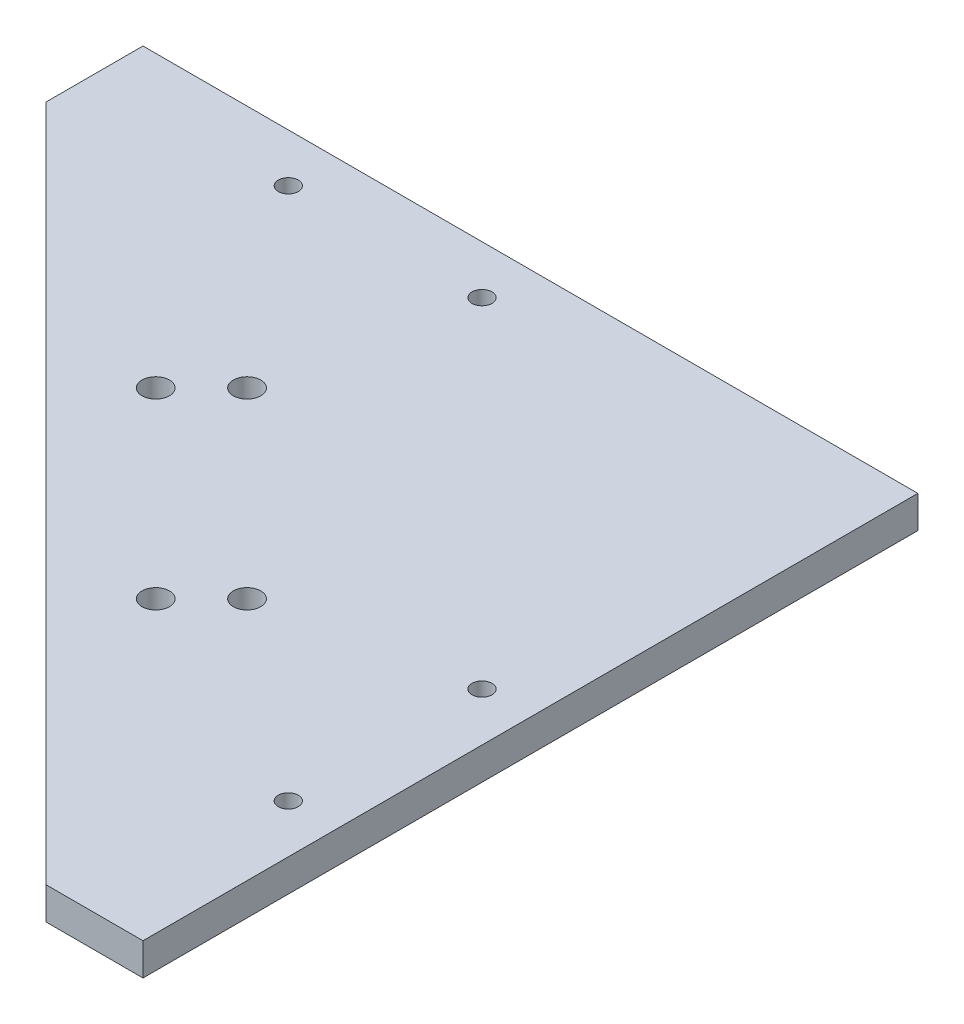
SolidWorks part; units mm, degrees
ref_plane "Front Plane" through (0, 0, 0) normal (0, 0, 1) x (1, 0, 0)
ref_plane "Top Plane" through (0, 0, 0) normal (0, 1, 0) x (1, 0, 0)
ref_plane "Right Plane" through (0, 0, 0) normal (1, 0, 0) x (0, 0, -1)
sketch "Sketch2" plane through (0, 0, 0) normal (0, 1, 0) x (1, 0, 0)
  line L0 (-120, -15) -> (-15, -120)
  line L1 (0, 0) -> (-120, 0)
  line L2 (0, 0) -> (0, -120)
  line L3 (0, -120) -> (-15, -120)
  line L4 (-120, 0) -> (-120, -15)
  dimension "D1" = 120
  dimension "D2" = 120
  dimension "D3" = 15
  dimension "D4" = 15
extrude "Boss-Extrude1" add sketch "Sketch2" along normal blind 5
sketch "Sketch3" plane through (0, 5, 0) normal (0, 1, 0) x (1, 0, 0)
  line L0 (-120, -7.5) -> (8.5201, -7.5) construction
  line L1 (-120, 0) -> (-120, -15) construction
  line L2 (-7.5, -120) -> (-7.5, 0) construction
  line L3 (-15, -120) -> (0, -120) construction
  line L4 (-55, 0) -> (55, 0) construction
  circle A0 centre (-90, -7.5) radius 1.55
  circle A1 centre (-60, -7.5) radius 1.55
  circle A2 centre (-7.5, -90) radius 1.55
  circle A3 centre (-7.5, -60) radius 1.55
  dimension "D1" = 3.1
  dimension "D2" = 3.1
  dimension "D3" = 3.1
  dimension "D4" = 3.1
  dimension "D5" = 30
  dimension "D6" = 30
  dimension "D7" = 30
  dimension "D8" = 30
extrude "Cut-Extrude1" cut sketch "Sketch3" against normal blind 5
sketch "Sketch4" plane through (0, 5, 0) normal (0, 1, 0) x (1, 0, 0)
  line L0 (-67.5, -67.5) -> (0, 0) construction
  line L1 (-120, -15) -> (-15, -120) construction
  line L2 (-73.1569, -44.8726) -> (-26.6384, 1.6458) construction
  circle A0 centre (-66.0858, -37.8015) radius 2.125
  circle A1 centre (-73.1569, -44.8726) radius 2.125
  circle A2 centre (-44.8726, -73.1569) radius 2.125
  circle A3 centre (-37.8015, -66.0858) radius 2.125
  dimension "D1" = 4.25
  dimension "D2" = 4.25
  dimension "D3" = 12
  dimension "D4" = 10
  dimension "D5" = 0
  dimension "D6" = 20
extrude "Cut-Extrude2" cut sketch "Sketch4" against normal blind 5
equation "\"D2@Sketch3\"=\"D1@Sketch3\""
equation "\"D3@Sketch3\"=\"D1@Sketch3\""
equation "\"D4@Sketch3\"=\"D1@Sketch3\""
equation "\"D6@Sketch3\"=\"D5@Sketch3\""
equation "\"D7@Sketch3\"=\"D5@Sketch3\""
equation "\"D8@Sketch3\"=\"D5@Sketch3\""
equation "\"D2@Sketch4\"=\"D1@Sketch4\""
